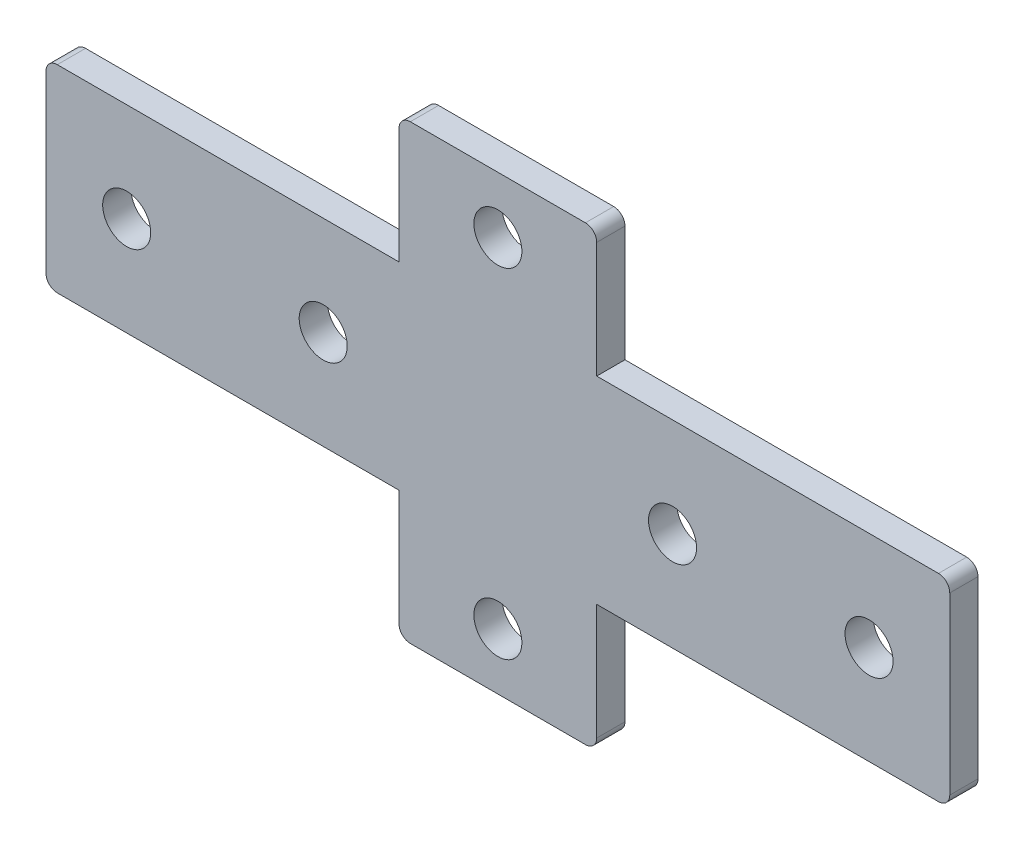
SolidWorks part; units mm, degrees
ref_plane "前视基准面" through (0, 0, 0) normal (0, 0, 1) x (1, 0, 0)
ref_plane "上视基准面" through (0, 0, 0) normal (0, 1, 0) x (1, 0, 0)
ref_plane "右视基准面" through (0, 0, 0) normal (1, 0, 0) x (0, 0, -1)
sketch "草图1" plane through (0, 0, 0) normal (0, 0, 1) x (1, 0, 0)
  line L0 (17.5, 17.5) -> (80, 17.5)
  line L1 (-80, -17.5) -> (-17.5, -17.5)
  line L2 (-80, -17.5) -> (-80, 17.5)
  line L3 (-80, 17.5) -> (-17.5, 17.5)
  line L4 (80, -17.5) -> (80, 17.5)
  line L5 (-80, -17.5) -> (80, 17.5) construction
  line L6 (-80, 17.5) -> (80, -17.5) construction
  line L7 (-17.5, -40) -> (17.5, -40)
  line L8 (-17.5, -40) -> (-17.5, -17.5)
  line L9 (-17.5, 40) -> (17.5, 40)
  line L10 (17.5, -40) -> (17.5, -17.5)
  line L11 (-17.5, -40) -> (17.5, 40) construction
  line L12 (-17.5, 40) -> (17.5, -40) construction
  line L13 (17.5, 17.5) -> (17.5, 40)
  line L14 (17.5, -17.5) -> (80, -17.5)
  line L15 (-17.5, 17.5) -> (-17.5, 40)
  point P0 (0, 0)
  point P6 (0, 0)
  dimension "D1" = 160
  dimension "D2" = 35
  dimension "D3" = 35
  dimension "D4" = 80
extrude "凸台-拉伸1" add sketch "草图1" along normal blind 5
fillet "圆角1" radius 2 8 edges at (-17.5, 40, 2.5) (17.5, 40, 2.5) (80, 17.5, 2.5) (80, -17.5, 2.5) (17.5, -40, 2.5) (-17.5, -40, 2.5) (-80, 17.5, 2.5) (-80, -17.5, 2.5)
sketch "草图2" plane through (0, 0, 5) normal (0, 0, 1) x (1, 0, 0)
  circle A0 centre (0, 30) radius 4.25
  circle A1 centre (-65.7128, 0) radius 4.25
  circle A2 centre (-30.9234, 0) radius 4.25
  dimension "D1" = 8.5
  dimension "D3" = 8.5
  dimension "D4" = 8.5
  dimension "D2" = 30
extrude "切除-拉伸1" cut sketch "草图2" against normal through all
mirror "镜向1" about plane through (0, 0, 0) normal (0, 1, 0) of "切除-拉伸1"
mirror "镜向2" about plane through (0, 0, 0) normal (1, 0, 0) of "切除-拉伸1"
